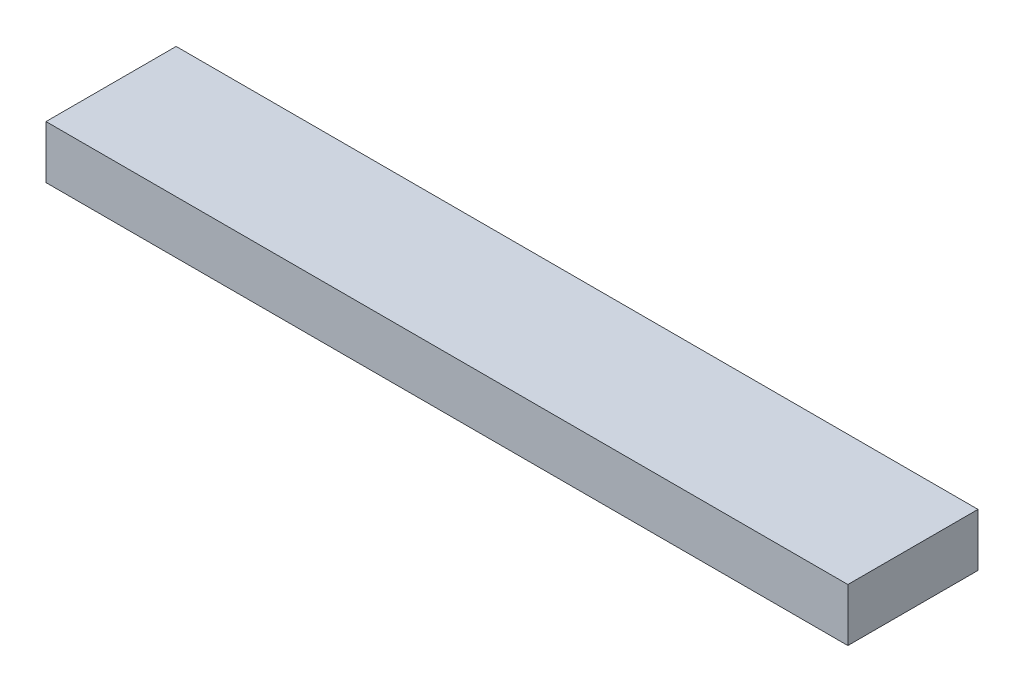
SolidWorks part; units mm, degrees
ref_plane "Front Plane" through (0, 0, 0) normal (0, 0, 1) x (1, 0, 0)
ref_plane "Top Plane" through (0, 0, 0) normal (0, 1, 0) x (1, 0, 0)
ref_plane "Right Plane" through (0, 0, 0) normal (1, 0, 0) x (0, 0, -1)
sketch "Sketch1" plane through (0, 0, 0) normal (0, 1, 0) x (1, 0, 0)
  line L1 (-23.875, 3.875) -> (23.875, 3.875)
  line L2 (-23.875, 3.875) -> (-23.875, -3.875)
  line L3 (-23.875, -3.875) -> (23.875, -3.875)
  line L4 (23.875, 3.875) -> (23.875, -3.875)
  line L5 (-23.875, 3.875) -> (23.875, -3.875) construction
  line L6 (-23.875, -3.875) -> (23.875, 3.875) construction
  point P0 (0, 0)
  dimension "D1" = 47.75
  dimension "D2" = 7.75
extrude "Boss-Extrude1" add sketch "Sketch1" against normal blind 3.15
shell "Shell1" thickness 1.5
sketch "Sketch2" plane through (0, -1.5, 0) normal (0, -1, 0) x (1, 0, 0)
  line L0 (-23.875, 3.875) -> (23.875, 3.875) construction
  line L1 (-23.875, -3.875) -> (-23.875, 3.875) construction
  circle A0 centre (-15.9583, 0) radius 1.5
  circle A1 centre (-15.9583, 0) radius 0.7
  circle A2 centre (-8, 0) radius 1.5
  circle A3 centre (-8, 0) radius 0.7
  circle A4 centre (-0.0417, 0) radius 1.5
  circle A5 centre (-0.0417, 0) radius 0.7
  circle A6 centre (7.9167, 0) radius 1.5
  circle A7 centre (7.9167, 0) radius 0.7
  circle A8 centre (15.875, 0) radius 1.5
  circle A9 centre (15.875, 0) radius 0.7
  dimension "D4" = 3
  dimension "D5" = 1.4
  dimension "D6" = 7.9583
  dimension "D1" = 3.875
  dimension "D2" = 7.9167
  dimension "D3" = 5
extrude "Boss-Extrude2" add sketch "Sketch2" along normal offset from surface (1.45 mm away) 0.2 up to face at (0, -3.15, 0)
